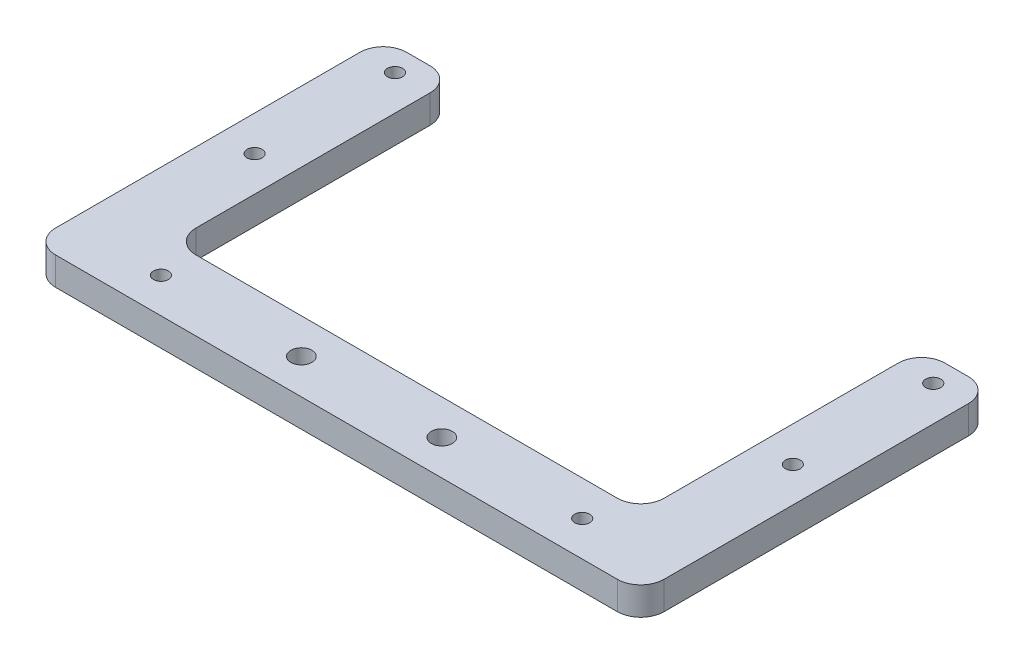
SolidWorks part; units mm, degrees
ref_plane "Front Plane" through (0, 0, 0) normal (0, 0, 1) x (1, 0, 0)
ref_plane "Top Plane" through (0, 0, 0) normal (0, 1, 0) x (1, 0, 0)
ref_plane "Right Plane" through (0, 0, 0) normal (1, 0, 0) x (0, 0, -1)
sketch "Sketch1" plane through (0, 0, 0) normal (0, 1, 0) x (1, 0, 0)
  line L0 (0, 0) -> (-50, 0)
  line L1 (-50, 0) -> (-50, 60)
  line L2 (-50, 60) -> (-65, 60)
  line L3 (-65, 60) -> (-65, -15)
  line L4 (-65, -15) -> (0, -15)
  line L5 (0, -15) -> (0, 0)
  dimension "D1" = 65
  dimension "D2" = 60
  dimension "D3" = 15
extrude "Boss-Extrude1" add sketch "Sketch1" along normal blind 6
fillet "Fillet1" radius 5 4 edges at (-65, 3, 15) (-65, 3, -60) (-50, 3, -60) (-50, 3, 0)
sketch "Sketch2" plane through (0, 6, 0) normal (0, 1, 0) x (1, 0, 0)
  line L0 (-15, 0) -> (-15, -15) construction
  line L1 (0, 0) -> (-45, 0) construction
  line L2 (-60, -15) -> (0, -15) construction
  line L3 (-65, 55) -> (-50, 55) construction
  circle A0 centre (-15, -7.5) radius 2.25
  circle A1 centre (-45, -7.5) radius 1.6
  circle A2 centre (-57.5, 55) radius 1.6
  circle A3 centre (-57.5, 25) radius 1.6
  arc A4 (-60, 60) -> (-65, 55) centre (-60, 55) ccw construction
  point P16 (0, 0)
  point P23 (0, 0)
  dimension "D1" = 4.5
  dimension "D3" = 3.2
  dimension "D4" = 3.2
  dimension "D2" = 15
  dimension "D5" = 30
extrude "Cut-Extrude1" cut sketch "Sketch2" against normal through all
mirror "Mirror1" about plane through (0, 0, 0) normal (1, 0, 0) of "Cut-Extrude1", "Boss-Extrude1", "Fillet1"
